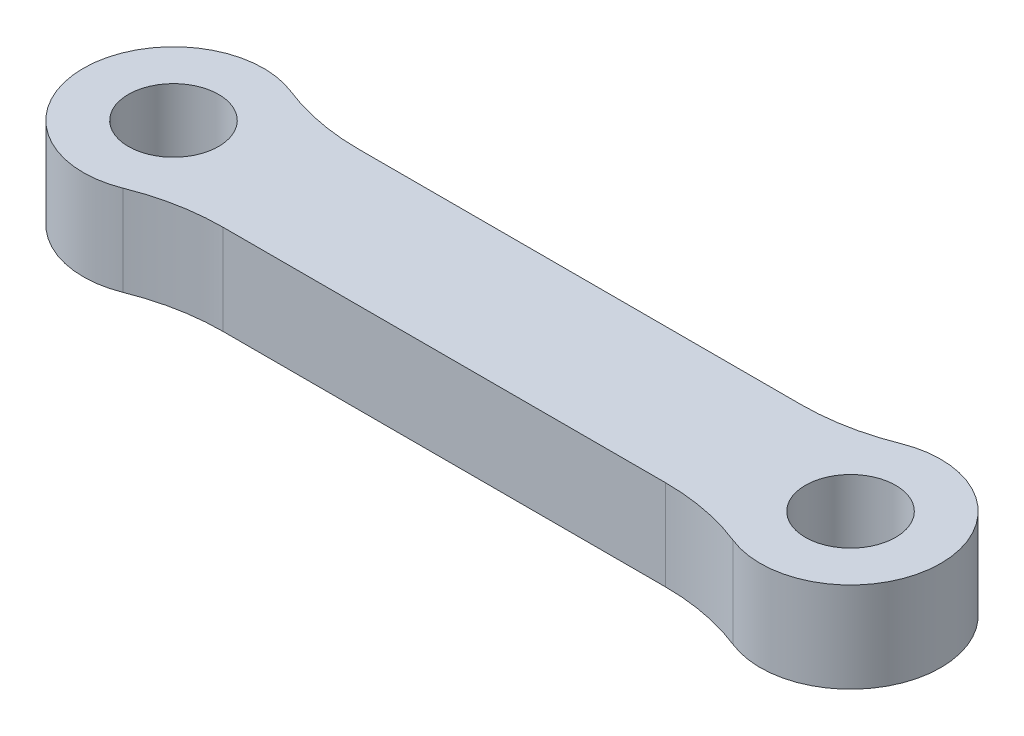
SolidWorks part; units mm, degrees
material "ABS PC"
ref_plane "Plan de face" through (0, 0, 0) normal (0, 0, 1) x (1, 0, 0)
ref_plane "Plan de dessus" through (0, 0, 0) normal (0, 1, 0) x (1, 0, 0)
ref_plane "Plan de droite" through (0, 0, 0) normal (1, 0, 0) x (0, 0, -1)
sketch "Esquisse1" plane through (0, 0, 0) normal (0, 1, 0) x (1, 0, 0)
  line L0 (2.6458, 3) -> (27.3542, 3)
  line L1 (2.6458, -3) -> (27.3542, -3)
  line L2 (0, 0) -> (30, 0) construction
  arc A2 (2.6458, 3) -> (2.6458, -3) centre (0, 0) ccw
  arc A3 (27.3542, 3) -> (27.3542, -3) centre (30, 0) cw
  circle A4 centre (0, 0) radius 2
  circle A5 centre (30, 0) radius 2
  dimension "D1" = 4
  dimension "D2" = 4
  dimension "D3" = 6
  dimension "D5" = 4
  dimension "D6" = 4
  dimension "D4" = 30
extrude "Boss.-Extru.1" add sketch "Esquisse1" along normal blind 4
fillet "Congé1" radius 10 4 edges at (27.3542, 2, -3) (2.6458, 2, -3) (27.3542, 2, 3) (2.6458, 2, 3)
